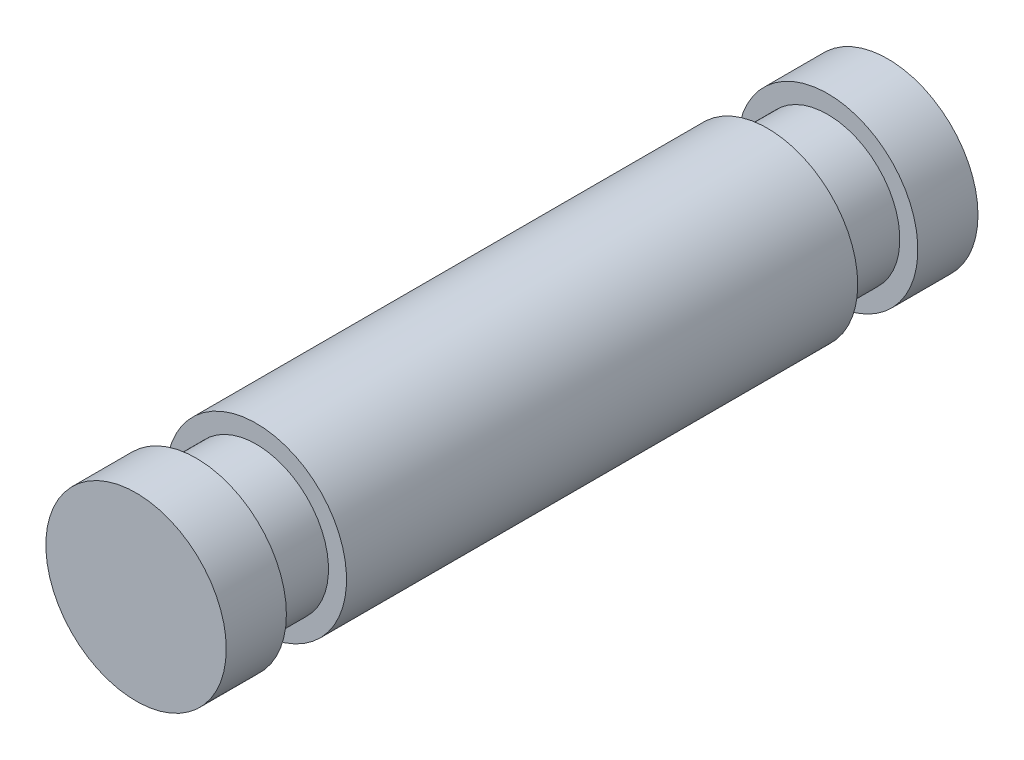
SolidWorks part; units mm, degrees
material "Cast Alloy Steel"
ref_plane "Front" through (0, 0, 0) normal (0, 0, 1) x (1, 0, 0)
ref_plane "Top" through (0, 0, 0) normal (0, 1, 0) x (1, 0, 0)
ref_plane "Right" through (0, 0, 0) normal (1, 0, 0) x (0, 0, -1)
sketch "Sketch1" plane through (0, 0, 0) normal (0, 0, 1) x (1, 0, 0)
  circle A0 centre (0, 0) radius 1.5
  dimension "D1" = 3
extrude "Boss-Extrude1" add sketch "Sketch1" along normal blind 12.5
sketch "Sketch2" plane through (0, 0, 0) normal (1, 0, 0) x (0, 0, -1)
  line L0 (0, -1.5) -> (0, 1.5) construction
  line L1 (-1, 1.2) -> (-2, 1.2)
  line L2 (-1, 1.2) -> (-1, 3.1372)
  line L3 (-1, 3.1372) -> (-2, 3.1372)
  line L4 (-2, 1.2) -> (-2, 3.1372)
  line L5 (0, 1.5) -> (-12.5, 1.5) construction
  line L6 (0, 0) -> (-6.25, 0) construction
  dimension "D1" = 1
  dimension "D2" = 1
  dimension "D3" = 0.3
revolve "Cut-Revolve1" cut sketch "Sketch2" angle 360 about L6
ref_plane "Plane1" through (0, 0, 6.25) normal (0, 0, 1) x (1, 0, 0)
mirror "Mirror1" about plane through (0, 0, 6.25) normal (0, 0, 1) of "Cut-Revolve1"
